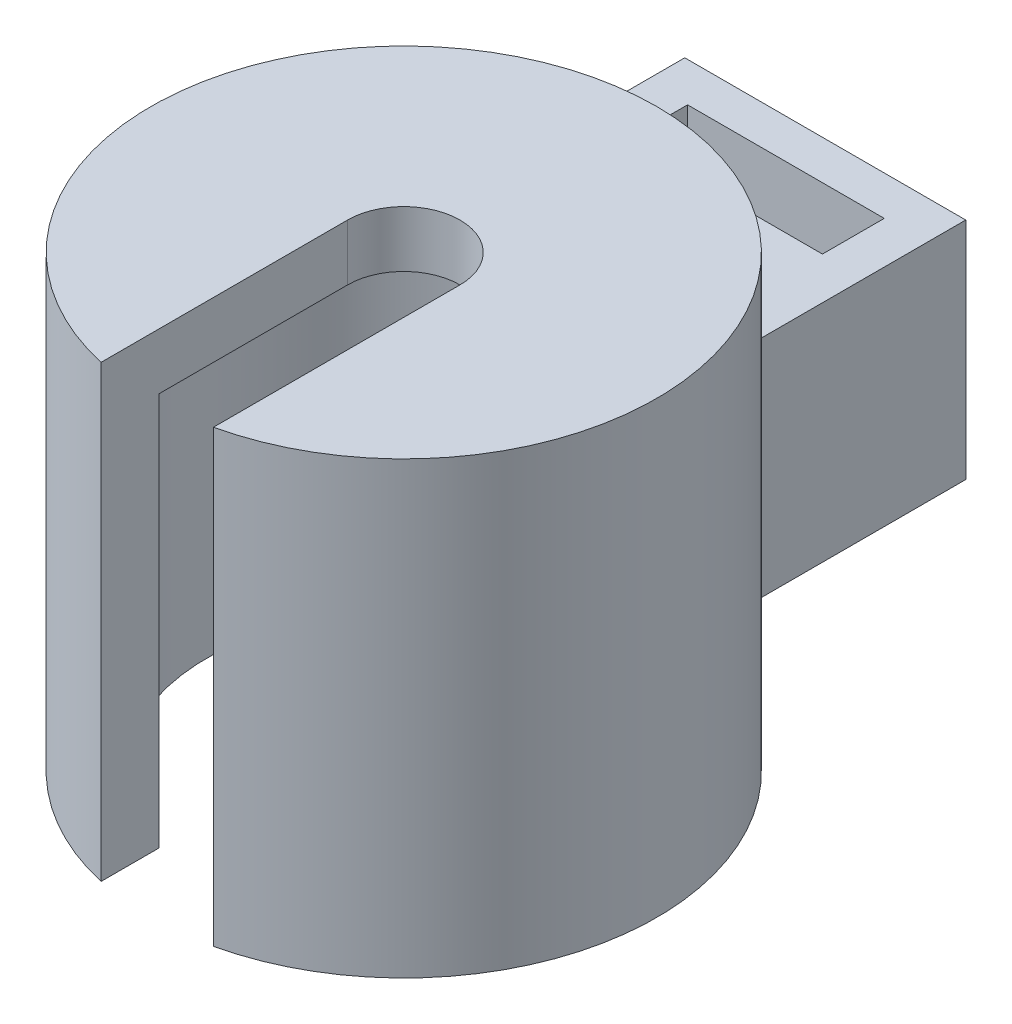
SolidWorks part; units mm, degrees
ref_plane "Front Plane" through (0, 0, 0) normal (0, 0, 1) x (1, 0, 0)
ref_plane "Top Plane" through (0, 0, 0) normal (0, 1, 0) x (1, 0, 0)
ref_plane "Right Plane" through (0, 0, 0) normal (1, 0, 0) x (0, 0, -1)
sketch "Sketch1" plane through (0, 0, 0) normal (0, 1, 0) x (1, 0, 0)
  line L1 (-1, 0) -> (1, 0)
  line L2 (-1, 0) -> (-1, -6.3229)
  line L3 (-1, -6.3229) -> (1, -6.3229)
  line L4 (1, 0) -> (1, -6.3229)
  circle A0 centre (0, 0) radius 3.5
  circle A1 centre (0, 0) radius 4.5
  circle A2 centre (0, 0) radius 1
  dimension "D1" = 7
  dimension "D2" = 9
  dimension "D3" = 2
  dimension "D4" = 2
extrude "Boss-Extrude1" add sketch "Sketch1" along normal blind 7 contours L4 A1 L2 A0
sketch "Sketch2" plane through (0, 7, 0) normal (0, 1, 0) x (1, 0, 0)
  line L1 (-1, 0) -> (1, 0)
  line L2 (-1, 0) -> (-1, -6.0985)
  line L3 (-1, -6.0985) -> (1, -6.0985)
  line L4 (1, 0) -> (1, -6.0985)
  circle A0 centre (0, 0) radius 5.25
  circle A1 centre (0, 0) radius 1
  line M7 (1, -3.3541) -> (1, -4.3875)
  arc M8 (1, -4.3875) -> (-1, -4.3875) centre (0, 0) ccw
  line M9 (-1, -4.3875) -> (-1, -3.3541)
  arc M10 (-1, -3.3541) -> (1, -3.3541) centre (0, 0) cw
  dimension "D1" = 2
  dimension "D2" = 2
extrude "Boss-Extrude2" add sketch "Sketch2" along normal blind 1 contours A1 L4 L2 M10 | M10 M7 M8 M9
sketch "Sketch3" plane through (0, 0, 0) normal (1, 0, 0) x (0, 0, -1)
  line L0 (4.5, 8) -> (4.5, 6)
  line L1 (4.5, 0) -> (4.5, 8) construction
  line L2 (4.5, 6) -> (3.5, 6)
  line L4 (3.5, 6) -> (7.5, 6)
  line L5 (3.5, 6) -> (3.5, 2)
  line L6 (3.5, 2) -> (7.5, 2)
  line L7 (7.5, 6) -> (7.5, 2)
  dimension "D1" = 2
  dimension "D2" = 1
  dimension "D3" = 4
  dimension "D4" = 4
extrude "Boss-Extrude3" add sketch "Sketch3" along normal blind 2.5 and the other way blind 2.5 contours L7 L4 L2 L5 L6
sketch "Sketch4" plane through (0, 6, 0) normal (0, 1, 0) x (1, 0, 0)
  line L0 (0, 7.5) -> (0, 6.8)
  line L1 (-2.5, 7.5) -> (2.5, 7.5) construction
  line L2 (0, -4.4) -> (0, 4.4) construction
  line L3 (0, 6.8) -> (1.75, 6.8)
  line L5 (1.75, 6.8) -> (-1.75, 6.8)
  line L6 (1.75, 6.8) -> (1.75, 5.7)
  line L7 (1.75, 5.7) -> (-1.75, 5.7)
  line L8 (-1.75, 6.8) -> (-1.75, 5.7)
  dimension "D1" = 0.7
  dimension "D2" = 1.75
  dimension "D3" = 3.5
  dimension "D4" = 1.1
extrude "Cut-Extrude1" cut sketch "Sketch4" against normal blind 7 contours L5 L8 L7 L6 L3
